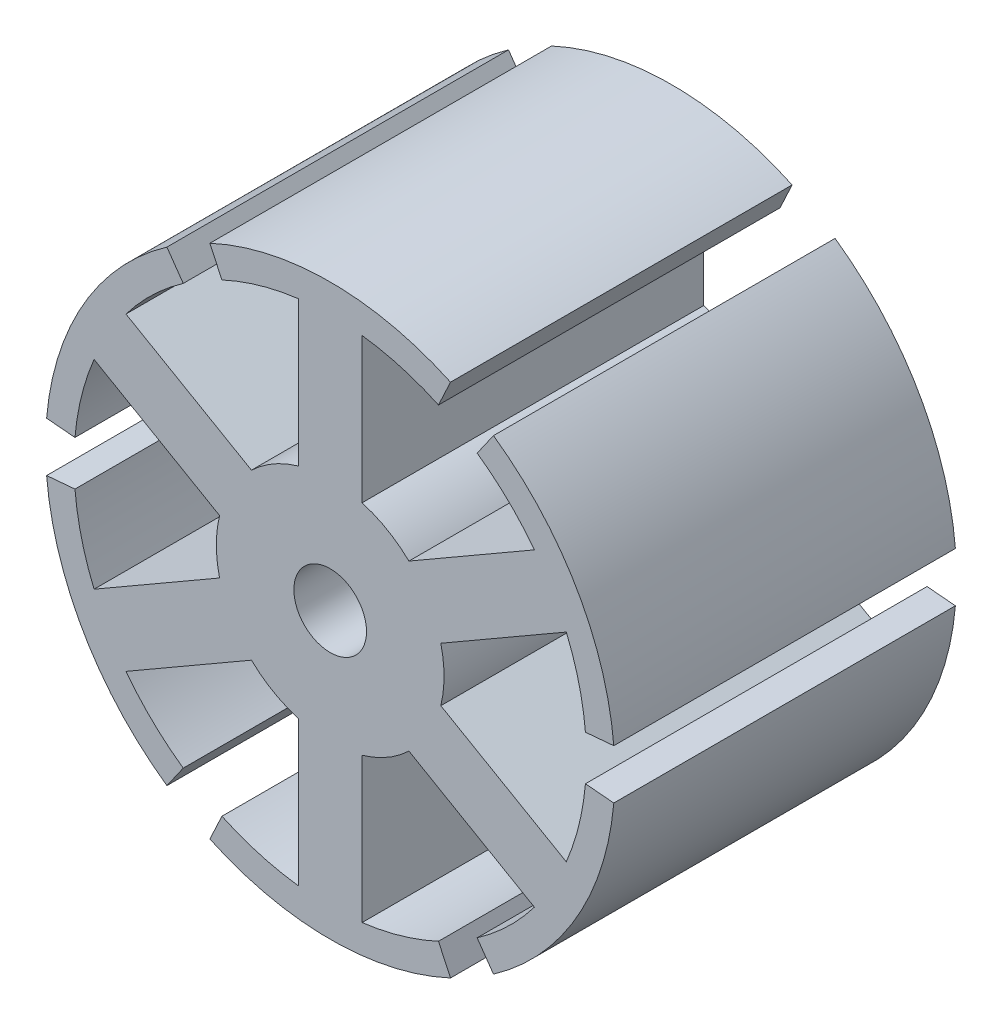
SolidWorks part; units mm, degrees
ref_plane "Front" through (0, 0, 0) normal (0, 0, 1) x (1, 0, 0)
ref_plane "Top" through (0, 0, 0) normal (0, 1, 0) x (1, 0, 0)
ref_plane "Right" through (0, 0, 0) normal (1, 0, 0) x (0, 0, -1)
sketch "Sketch1" plane through (0, 0, 0) normal (0, 0, 1) x (1, 0, 0)
  line L0 (0, 0) -> (25, 0) construction
  line L1 (0, 0) -> (12.5, 21.6506) construction
  line L2 (0, 0) -> (-12.5, 21.6506) construction
  line L3 (0, 0) -> (-25, 0) construction
  line L5 (0, 0) -> (-12.5, -21.6506) construction
  line L6 (0, 0) -> (12.5, -21.6506) construction
  line L7 (0, 0) -> (21.6506, 12.5) construction
  line L8 (5.6, 0) -> (20.7341, 8.7377) construction
  line L9 (2.8, 4.8497) -> (17.9341, 13.5874) construction
  line L10 (0, 0) -> (23.3491, 8.9342) construction
  line L14 (0, 0) -> (24.9049, 2.1789) construction
  line L16 (0, 0) -> (10.5655, 22.6577) construction
  line L17 (0, 0) -> (24.9049, -2.1789) construction
  line L18 (0, 0) -> (14.3394, 20.4788) construction
  circle A4 centre (0, 0) radius 25 construction
  circle A5 centre (0, 0) radius 22.5 construction
  circle A7 centre (0, 0) radius 10 construction
  dimension "D1" = 20
  dimension "D2" = 5.6
  dimension "D3" = 50
  dimension "D4" = 45
  dimension "D5" = 2.5
sketch "Sketch2" plane through (0, 0, 0) normal (0, 0, 1) x (1, 0, 0)
  circle A2 centre (0, 0) radius 25
  point P1 (0, 0)
extrude "Boss-Extrude2" add sketch "Sketch2" along normal blind 30
sketch "Sketch3" plane through (0, 0, 30) normal (0, 0, 1) x (1, 0, 0)
  line L0 (17.9341, 13.5874) -> (6.9138, 7.2249) construction
  line L1 (2.8, 4.8497) -> (17.9341, 13.5874) construction
  line L2 (20.7341, 8.7377) -> (9.7138, 2.3751) construction
  line L3 (5.6, 0) -> (20.7341, 8.7377) construction
  line L4 (24.9049, 2.1789) -> (22.4144, 1.961) construction
  line L5 (0, 0) -> (24.9049, 2.1789) construction
  line L6 (14.3394, 20.4788) -> (12.9055, 18.4309) construction
  line L7 (0, 0) -> (14.3394, 20.4788) construction
  line L8 (6.9138, -7.2249) -> (17.9341, -13.5874)
  line L9 (2.8, -9.6) -> (2.8, -22.3251)
  line L30 (20.7341, -8.7377) -> (9.7138, -2.3751) construction
  line L31 (17.9341, -13.5874) -> (6.9138, -7.2249) construction
  line L32 (14.3394, -20.4788) -> (12.9055, -18.4309) construction
  line L33 (24.9049, -2.1789) -> (22.4144, -1.961) construction
  line L34 (2.8, -22.3251) -> (2.8, -9.6) construction
  line L35 (-2.8, -22.3251) -> (-2.8, -9.6) construction
  line L36 (-10.5655, -22.6577) -> (-9.5089, -20.3919) construction
  line L37 (10.5655, -22.6577) -> (9.5089, -20.3919) construction
  line L38 (-17.9341, -13.5874) -> (-6.9138, -7.2249) construction
  line L39 (-20.7341, -8.7377) -> (-9.7138, -2.3751) construction
  line L40 (-24.9049, -2.1789) -> (-22.4144, -1.961) construction
  line L41 (-14.3394, -20.4788) -> (-12.9055, -18.4309) construction
  line L42 (-20.7341, 8.7377) -> (-9.7138, 2.3751) construction
  line L43 (-17.9341, 13.5874) -> (-6.9138, 7.2249) construction
  line L44 (-14.3394, 20.4788) -> (-12.9055, 18.4309) construction
  line L45 (-24.9049, 2.1789) -> (-22.4144, 1.961) construction
  line L46 (-2.8, 22.3251) -> (-2.8, 9.6) construction
  line L47 (2.8, 22.3251) -> (2.8, 9.6) construction
  line L48 (10.5655, 22.6577) -> (9.5089, 20.3919) construction
  line L49 (-10.5655, 22.6577) -> (-9.5089, 20.3919) construction
  line L50 (9.7138, -2.3751) -> (20.7341, -8.7377)
  line L51 (9.7138, 2.3751) -> (20.7341, 8.7377)
  line L52 (22.4144, 1.961) -> (24.9049, 2.1789)
  line L53 (22.4144, -1.961) -> (24.9049, -2.1789)
  line L54 (12.9055, -18.4309) -> (14.3394, -20.4788)
  line L55 (9.5089, -20.3919) -> (10.5655, -22.6577)
  line L56 (-2.8, -9.6) -> (-2.8, -22.3251)
  line L57 (-6.9138, -7.2249) -> (-17.9341, -13.5874)
  line L58 (-9.5089, -20.3919) -> (-10.5655, -22.6577)
  line L59 (-12.9055, -18.4309) -> (-14.3394, -20.4788)
  line L60 (-9.7138, -2.3751) -> (-20.7341, -8.7377)
  line L61 (-9.7138, 2.3751) -> (-20.7341, 8.7377)
  line L62 (-22.4144, -1.961) -> (-24.9049, -2.1789)
  line L63 (-22.4144, 1.961) -> (-24.9049, 2.1789)
  line L64 (-6.9138, 7.2249) -> (-17.9341, 13.5874)
  line L65 (-2.8, 9.6) -> (-2.8, 22.3251)
  line L66 (-12.9055, 18.4309) -> (-14.3394, 20.4788)
  line L67 (-9.5089, 20.3919) -> (-10.5655, 22.6577)
  line L68 (2.8, 9.6) -> (2.8, 22.3251)
  line L69 (6.9138, 7.2249) -> (17.9341, 13.5874)
  line L70 (9.5089, 20.3919) -> (10.5655, 22.6577)
  line L71 (12.9055, 18.4309) -> (14.3394, 20.4788)
  circle A0 centre (0, 0) radius 10 construction
  circle A1 centre (0, 0) radius 22.5 construction
  arc A2 (14.3394, 20.4788) -> (24.9049, 2.1789) centre (0, 0) cw construction
  arc A3 (12.9055, 18.4309) -> (17.9341, 13.5874) centre (0, 0) cw construction
  arc A4 (20.7341, 8.7377) -> (22.4144, 1.961) centre (0, 0) cw construction
  arc A26 (24.9049, -2.1789) -> (14.3394, -20.4788) centre (0, 0) cw construction
  arc A27 (22.4144, -1.961) -> (20.7341, -8.7377) centre (0, 0) cw construction
  arc A28 (17.9341, -13.5874) -> (12.9055, -18.4309) centre (0, 0) cw construction
  arc A29 (10.5655, -22.6577) -> (-10.5655, -22.6577) centre (0, 0) cw construction
  arc A30 (9.5089, -20.3919) -> (2.8, -22.3251) centre (0, 0) cw construction
  arc A31 (-2.8, -22.3251) -> (-9.5089, -20.3919) centre (0, 0) cw construction
  arc A32 (-14.3394, -20.4788) -> (-24.9049, -2.1789) centre (0, 0) cw construction
  arc A33 (-12.9055, -18.4309) -> (-17.9341, -13.5874) centre (0, 0) cw construction
  arc A34 (-20.7341, -8.7377) -> (-22.4144, -1.961) centre (0, 0) cw construction
  arc A35 (-24.9049, 2.1789) -> (-14.3394, 20.4788) centre (0, 0) cw construction
  arc A36 (-22.4144, 1.961) -> (-20.7341, 8.7377) centre (0, 0) cw construction
  arc A37 (-17.9341, 13.5874) -> (-12.9055, 18.4309) centre (0, 0) cw construction
  arc A38 (-10.5655, 22.6577) -> (10.5655, 22.6577) centre (0, 0) cw construction
  arc A39 (-9.5089, 20.3919) -> (-2.8, 22.3251) centre (0, 0) cw construction
  arc A40 (2.8, 22.3251) -> (9.5089, 20.3919) centre (0, 0) cw construction
  arc A42 (9.7138, 2.3751) -> (9.7138, -2.3751) centre (0, 0) cw
  arc A43 (20.7341, 8.7377) -> (22.4144, 1.961) centre (0, 0) cw
  arc A44 (20.7341, -8.7377) -> (22.4144, -1.961) centre (0, 0) ccw
  arc A45 (24.9049, -2.1789) -> (24.9049, 2.1789) centre (0, 0) ccw
  arc A46 (6.9138, -7.2249) -> (2.8, -9.6) centre (0, 0) cw
  arc A47 (2.8, -22.3251) -> (9.5089, -20.3919) centre (0, 0) ccw
  arc A48 (17.9341, -13.5874) -> (12.9055, -18.4309) centre (0, 0) cw
  arc A49 (10.5655, -22.6577) -> (14.3394, -20.4788) centre (0, 0) ccw
  arc A50 (-2.8, -9.6) -> (-6.9138, -7.2249) centre (0, 0) cw
  arc A51 (-17.9341, -13.5874) -> (-12.9055, -18.4309) centre (0, 0) ccw
  arc A52 (-2.8, -22.3251) -> (-9.5089, -20.3919) centre (0, 0) cw
  arc A53 (-14.3394, -20.4788) -> (-10.5655, -22.6577) centre (0, 0) ccw
  arc A54 (-9.7138, -2.3751) -> (-9.7138, 2.3751) centre (0, 0) cw
  arc A55 (-20.7341, 8.7377) -> (-22.4144, 1.961) centre (0, 0) ccw
  arc A56 (-20.7341, -8.7377) -> (-22.4144, -1.961) centre (0, 0) cw
  arc A57 (-24.9049, 2.1789) -> (-24.9049, -2.1789) centre (0, 0) ccw
  arc A58 (-6.9138, 7.2249) -> (-2.8, 9.6) centre (0, 0) cw
  arc A59 (-2.8, 22.3251) -> (-9.5089, 20.3919) centre (0, 0) ccw
  arc A60 (-17.9341, 13.5874) -> (-12.9055, 18.4309) centre (0, 0) cw
  arc A61 (-10.5655, 22.6577) -> (-14.3394, 20.4788) centre (0, 0) ccw
  arc A62 (2.8, 9.6) -> (6.9138, 7.2249) centre (0, 0) cw
  arc A63 (17.9341, 13.5874) -> (12.9055, 18.4309) centre (0, 0) ccw
  arc A64 (2.8, 22.3251) -> (9.5089, 20.3919) centre (0, 0) cw
  arc A65 (14.3394, 20.4788) -> (10.5655, 22.6577) centre (0, 0) ccw
  point P68 (0, 0)
  point P129 (0, 0)
extrude "Cut-Extrude2" cut sketch "Sketch3" against normal blind 30
sketch "Sketch4" plane through (0, 0, 30) normal (0, 0, 1) x (1, 0, 0)
  circle A0 centre (0, 0) radius 3.19
extrude "Cut-Extrude3" cut sketch "Sketch4" against normal blind 30
